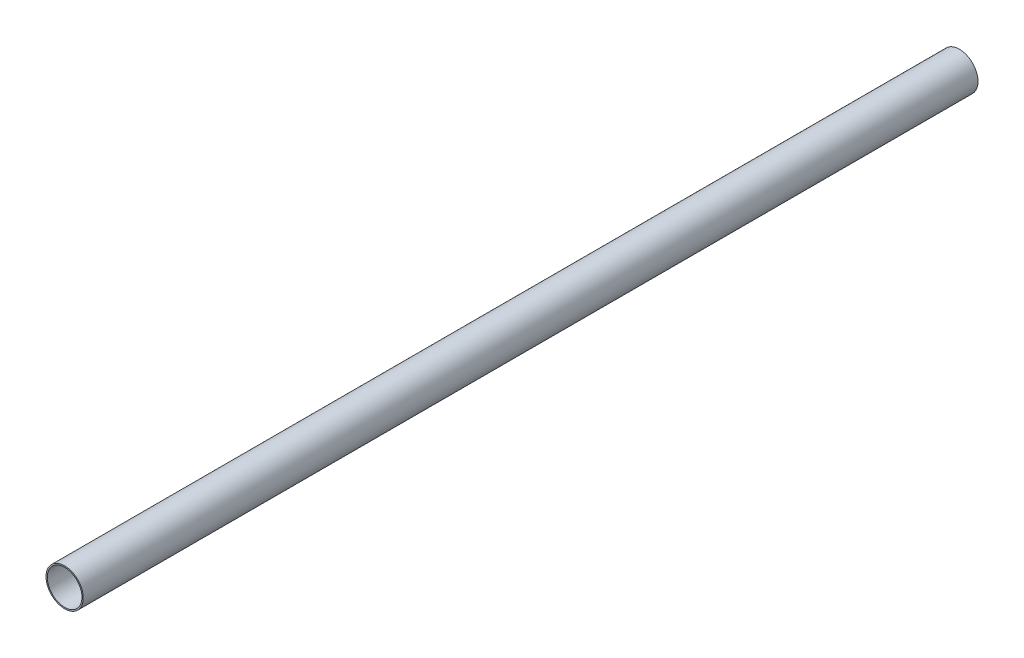
SolidWorks part; units mm, degrees
ref_plane "Front Plane" through (0, 0, 0) normal (0, 0, 1) x (1, 0, 0)
ref_plane "Top Plane" through (0, 0, 0) normal (0, 1, 0) x (1, 0, 0)
ref_plane "Right Plane" through (0, 0, 0) normal (1, 0, 0) x (0, 0, -1)
sketch "Sketch1" plane through (0, 0, 0) normal (0, 0, 1) x (1, 0, 0)
  line L0 (-12.7, 0) -> (12.7, 0) construction
  line L1 (0, -12.7) -> (0, 12.7) construction
  circle A0 centre (0, 0) radius 12.7
  circle A1 centre (0, 0) radius 11.811
  point P4 (0, 0)
  point P9 (0, 0)
  point P10 (11.811, 0)
  dimension "D1" = 23.622
  dimension "OD" = 25.4
  dimension "Wall Thickness" = 0.889
sketch "Sketch2" plane through (0, 0, 0) normal (1, 0, 0) x (0, 0, -1)
  line L0 (304.8, 12.7) -> (-304.8, 12.7) construction
  line L1 (0, 12.7) -> (0, -12.7) construction
  point P3 (-275.59, 12.7)
  point P4 (0, 12.7)
  point P5 (275.59, 12.7)
  dimension "D1" = 29.21
  dimension "D2" = 29.21
  dimension "Length" = 609.6
sketch "Sketch3" plane through (0, 0, 0) normal (0, 0, 1) x (1, 0, 0)
  line L0 (0, -12.7) -> (0, 12.7) construction
  circle A0 centre (0, 0) radius 12.7
  circle A1 centre (0, 0) radius 11.811
  circle A2 centre (0, 0) radius 11.811 construction
extrude "Boss-Extrude1" add sketch "Sketch3" along normal mid plane 609.6
equation "\"D1@Boss-Extrude1\" = \"Length@Sketch2\""
equation "\"D1@Sketch2\"=\"OD@Sketch1\"*1.15"
equation "\"D2@Sketch2\"=\"D1@Sketch2\""
